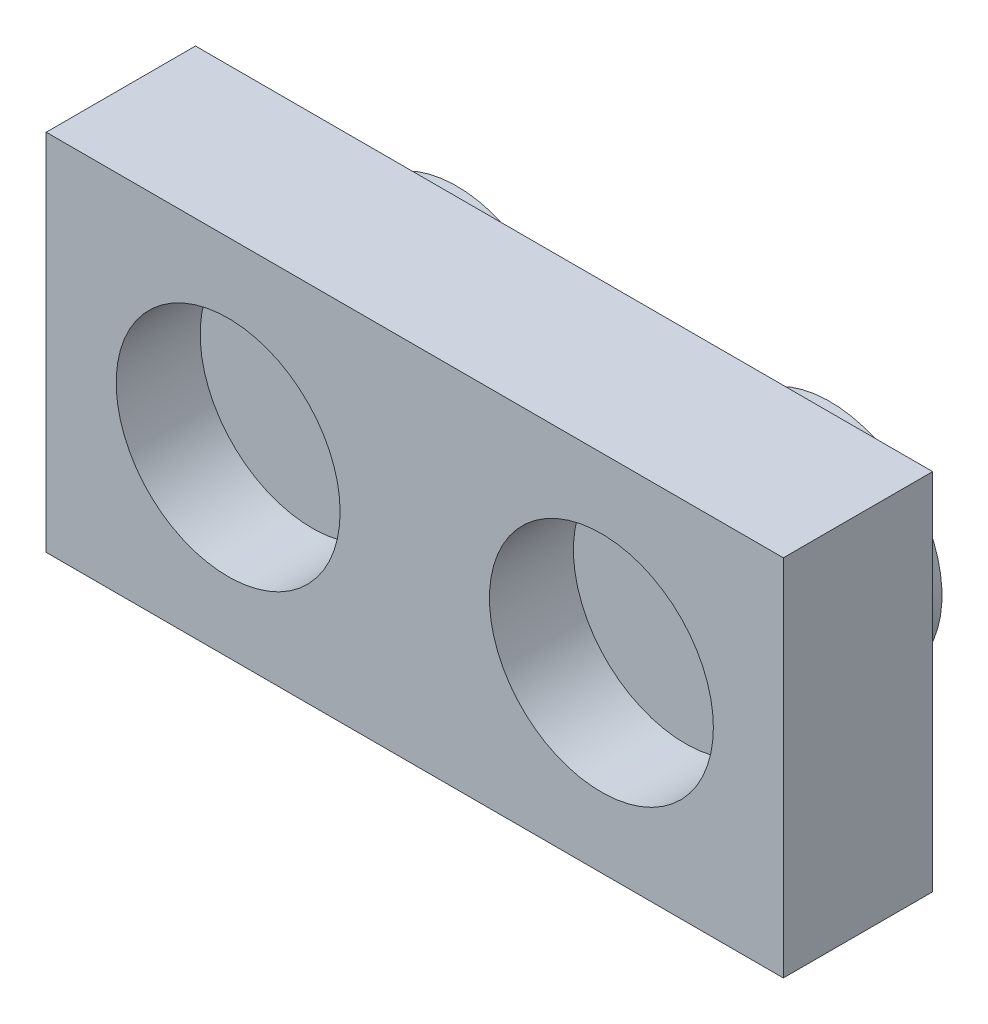
SolidWorks part; units mm, degrees
ref_plane "Спереди" through (0, 0, 0) normal (0, 0, 1) x (1, 0, 0)
ref_plane "Сверху" through (0, 0, 0) normal (0, 1, 0) x (1, 0, 0)
ref_plane "Справа" through (0, 0, 0) normal (1, 0, 0) x (0, 0, -1)
sketch "Эскиз3" plane through (0, 0, 0) normal (0, 0, 1) x (1, 0, 0)
  line L1 (-7.9, -3.9) -> (7.9, -3.9)
  line L2 (-7.9, -3.9) -> (-7.9, 3.9)
  line L3 (-7.9, 3.9) -> (7.9, 3.9)
  line L4 (7.9, -3.9) -> (7.9, 3.9)
  line L5 (-7.9, -3.9) -> (7.9, 3.9) construction
  line L6 (-7.9, 3.9) -> (7.9, -3.9) construction
  point P0 (0, 0)
  dimension "D1" = 15.8
  dimension "D2" = 7.8
extrude "Бобышка-Вытянуть2" add sketch "Эскиз3" along normal blind 3.2
sketch "Эскиз4" plane through (0, 0, 0) normal (0, 0, -1) x (-1, 0, 0)
  circle A0 centre (-4, 0) radius 2.4
  circle A1 centre (4, 0) radius 2.4
  point P4 (0, 0)
  dimension "D1" = 4.8
  dimension "D2" = 8
  dimension "D3" = 4
extrude "Бобышка-Вытянуть3" add sketch "Эскиз4" along normal blind 1.7
sketch "Эскиз5" plane through (0, 0, 3.2) normal (0, 0, 1) x (1, 0, 0)
  circle A0 centre (-4, 0) radius 2.4
  circle A1 centre (4, 0) radius 2.4
  dimension "D1" = 4
  dimension "D2" = 4
extrude "Вырез-Вытянуть1" cut sketch "Эскиз5" against normal blind 1.8
